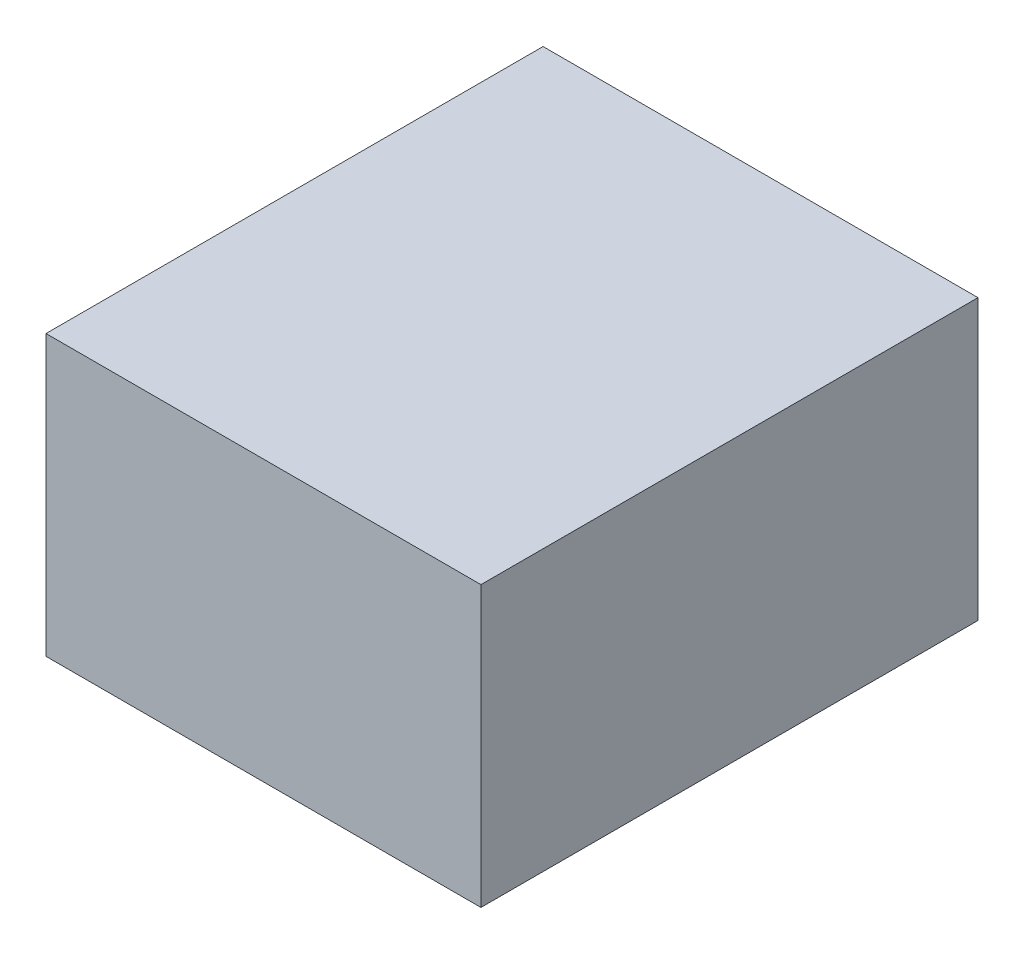
SolidWorks part; units mm, degrees
ref_plane "Front Plane" through (0, 0, 0) normal (0, 0, 1) x (1, 0, 0)
ref_plane "Top Plane" through (0, 0, 0) normal (0, 1, 0) x (1, 0, 0)
ref_plane "Right Plane" through (0, 0, 0) normal (1, 0, 0) x (0, 0, -1)
sketch "Sketch1" plane through (0, 0, 0) normal (0, 0, 1) x (1, 0, 0)
  line L1 (-100, -1875) -> (600, -1875)
  line L2 (-100, -1875) -> (-100, -1425)
  line L3 (-100, -1425) -> (600, -1425)
  line L4 (600, -1875) -> (600, -1425)
extrude "Boss-Extrude1" add sketch "Sketch1" along normal blind 800 from offset 400
